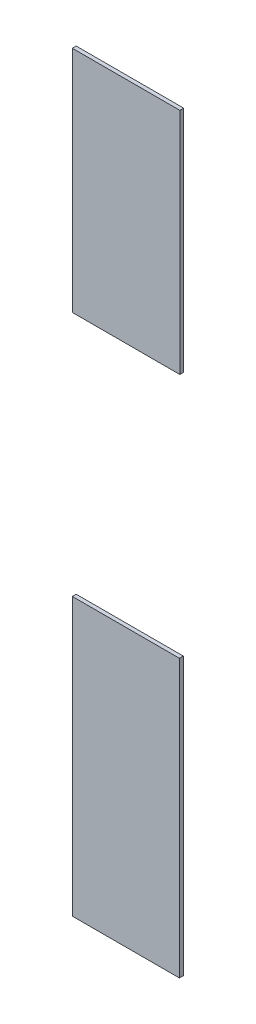
SolidWorks part; units mm, degrees
material "Гипс"
ref_plane "Спереди" through (0, 0, 0) normal (0, 0, 1) x (1, 0, 0)
ref_plane "Сверху" through (0, 0, 0) normal (0, 1, 0) x (1, 0, 0)
ref_plane "Справа" through (0, 0, 0) normal (1, 0, 0) x (0, 0, -1)
sketch "Эскиз3" plane through (0, 0, 0) normal (0, 0, 1) x (1, 0, 0)
  line L0 (-350, -745) -> (-350, 0) construction
  line L1 (0, 0) -> (-350, 0)
  line L2 (0, 0) -> (0, -744.25)
  line L3 (0, -744.25) -> (-350, -744.25)
  line L4 (-350, 0) -> (-350, -744.25)
  line L5 (-1600, -744.25) -> (0, -744.25) construction
  line L7 (-1.5, -1544.25) -> (-350, -1544.25)
  line L8 (-1.5, -1544.25) -> (-1.5, -2445)
  line L9 (-1.5, -2445) -> (-350, -2445)
  line L10 (-350, -1544.25) -> (-350, -2445)
extrude "Бобышка-Вытянуть1" add sketch "Эскиз3" along normal blind 12.5
